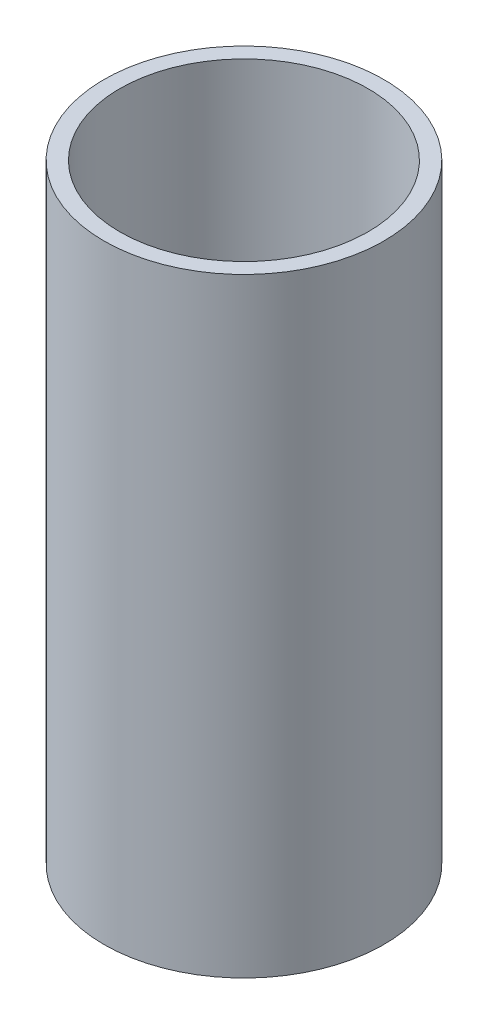
SolidWorks part; units mm, degrees
ref_plane "Front Plane" through (0, 0, 0) normal (0, 0, 1) x (1, 0, 0)
ref_plane "Top Plane" through (0, 0, 0) normal (0, 1, 0) x (1, 0, 0)
ref_plane "Right Plane" through (0, 0, 0) normal (1, 0, 0) x (0, 0, -1)
sketch "Sketch1" plane through (0, 0, 0) normal (0, 1, 0) x (1, 0, 0)
  circle A0 centre (0, 0) radius 27.5
  circle A1 centre (0, 0) radius 31
  dimension "D1" = 55
  dimension "D2" = 62
extrude "Boss-Extrude1" add sketch "Sketch1" along normal mid plane 135
